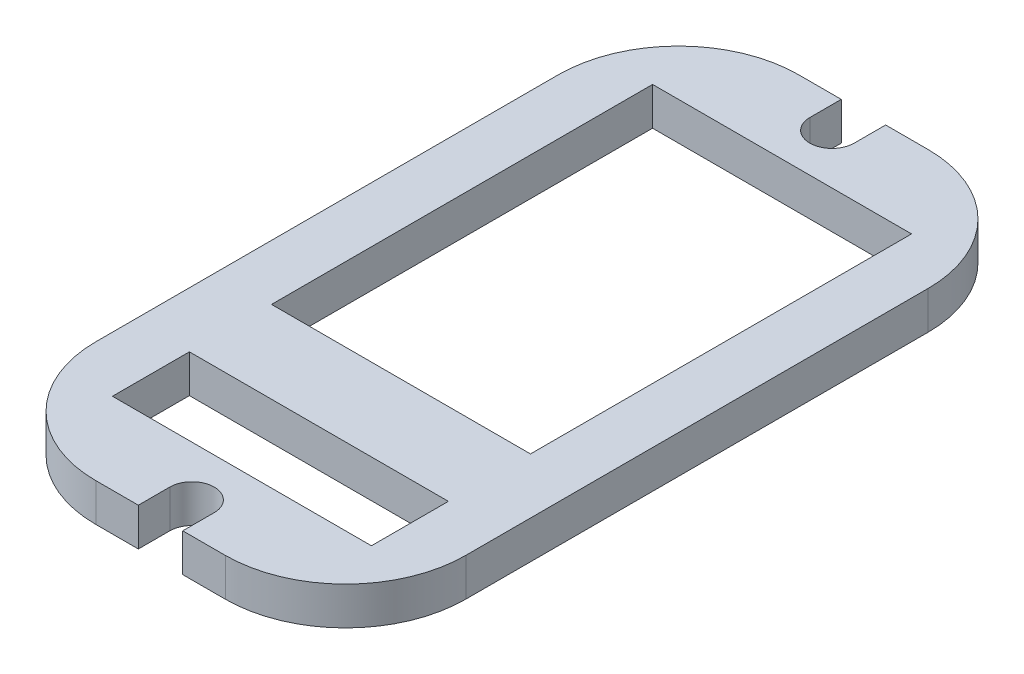
SolidWorks part; units mm, degrees
ref_plane "Front Plane" through (0, 0, 0) normal (0, 0, 1) x (1, 0, 0)
ref_plane "Top Plane" through (0, 0, 0) normal (0, 1, 0) x (1, 0, 0)
ref_plane "Right Plane" through (0, 0, 0) normal (1, 0, 0) x (0, 0, -1)
sketch "Sketch2" plane through (0, 0, 0) normal (0, 1, 0) x (1, 0, 0)
  line L0 (-0.6, 9.5) -> (-1.75, 9.5)
  line L1 (-5, 6.25) -> (-5, -6.25)
  line L2 (-1.75, -9.5) -> (-0.6, -9.5)
  line L3 (-3.5, -3) -> (3.5, -3)
  line L4 (3.5, -3) -> (3.5, 7.3)
  line L5 (3.5, 7.3) -> (-3.5, 7.3)
  line L6 (-3.5, 7.3) -> (-3.5, -3)
  line L7 (-3.5, -7.3) -> (3.5, -7.3)
  line L8 (3.5, -7.3) -> (3.5, -5.22)
  line L9 (3.5, -5.22) -> (-3.5, -5.22)
  line L10 (-3.5, -5.22) -> (-3.5, -7.3)
  line L11 (0, 8.65) -> (0, -8.65) construction
  line L12 (-0.6, -8.65) -> (-0.6, -9.5)
  line L13 (0.6, -8.65) -> (0.6, -9.5)
  line L14 (-0.6, 9.5) -> (-0.6, 8.65)
  line L15 (0.6, -9.5) -> (1.75, -9.5)
  line L16 (5, -6.25) -> (5, 6.25)
  line L17 (1.75, 9.5) -> (0.6, 9.5)
  line L18 (0, 0) -> (0, -3) construction
  line L19 (0, -3) -> (0, -5.22) construction
  line L20 (0.6, 9.5) -> (0.6, 8.65)
  arc A0 (-0.6, 8.65) -> (0.6, 8.65) centre (0, 8.65) ccw
  arc A1 (0.6, -8.65) -> (-0.6, -8.65) centre (0, -8.65) ccw
  arc A2 (-1.75, 9.5) -> (-5, 6.25) centre (-1.75, 6.25) ccw
  arc A3 (-5, -6.25) -> (-1.75, -9.5) centre (-1.75, -6.25) ccw
  arc A4 (1.75, -9.5) -> (5, -6.25) centre (1.75, -6.25) ccw
  arc A5 (5, 6.25) -> (1.75, 9.5) centre (1.75, 6.25) ccw
  point P30 (0, -5.22)
  point P31 (0, -3)
  point P38 (0, 0)
  dimension "D7" = 0.6
  dimension "D9" = 3.25
  dimension "D1" = 2.22
  dimension "D2" = 3
  dimension "D3" = 10.3
  dimension "D4" = 2.08
  dimension "D5" = 17.3
  dimension "D6" = 7
  dimension "D8" = 10
  dimension "D10" = 19
extrude "Boss-Extrude1" add sketch "Sketch2" along normal blind 1.026
